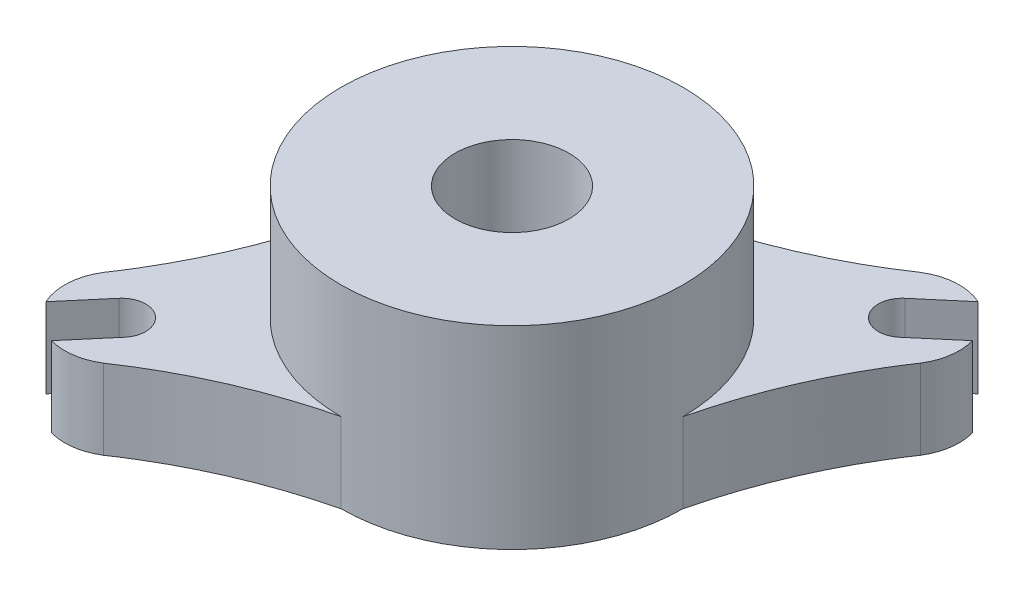
SolidWorks part; units mm, degrees
ref_plane "Front Plane" through (0, 0, 0) normal (0, 0, 1) x (1, 0, 0)
ref_plane "Top Plane" through (0, 0, 0) normal (0, 1, 0) x (1, 0, 0)
ref_plane "Right Plane" through (0, 0, 0) normal (1, 0, 0) x (0, 0, -1)
sketch "Sketch1" plane through (0, 0, 0) normal (0, 1, 0) x (1, 0, 0)
  line L0 (0, 0) -> (-25.3468, 25.3468) construction
  line L1 (21.7322, 21.7322) -> (-21.7322, -21.7322) construction
  circle A0 centre (0, 0) radius 19.05
  circle A1 centre (0, 0) radius 6.35
  circle A2 centre (21.7322, 21.7322) radius 2.667
  circle A3 centre (-21.7322, -21.7322) radius 2.667
  arc A4 (26.8844, 18.0205) -> (18.0205, 26.8844) centre (21.7322, 21.7322) ccw
  arc A5 (-26.8844, -18.0205) -> (-18.0205, -26.8844) centre (-21.7322, -21.7322) ccw
  spline S0 degree 2 poles (0, 19.05) (10.0975, 21.5258) (18.3794, 27.1249) knots 0 0 0 0.663462 0.663462 0.663462
  spline S1 degree 2 poles (19.05, 0) (21.5258, 10.0975) (27.1249, 18.3794) knots 0 0 0 0.663462 0.663462 0.663462
  spline S2 degree 2 poles (0, -19.05) (-10.0975, -21.5258) (-18.3794, -27.1249) knots 0 0 0 0.663462 0.663462 0.663462
  spline S3 degree 2 poles (-19.05, 0) (-21.5258, -10.0975) (-27.1249, -18.3794) knots 0 0 0 0.663462 0.663462 0.663462
  dimension "D1" = 38.1
  dimension "D2" = 12.7
  dimension "D5" = 5.334
  dimension "D6" = 5.334
  dimension "D7" = 12.7
  dimension "D8" = 12.7
  dimension "D3" = 30.734
  dimension "D4" = 30.734
extrude "Boss-Extrude1" add sketch "Sketch1" along normal blind 21.59 contours A0 A1 | A0 S3 A5 S2 A3 | A0 S1 A4 S0 A2
sketch "Sketch2" plane through (0, 21.59, 0) normal (0, 1, 0) x (1, 0, 0)
  circle A0 centre (0, 0) radius 19.05
  spline M4 degree 2 poles (19.05, 0) (21.5258, 10.0975) (27.1249, 18.3794) knots 0 0 0 0.663462 0.663462 0.663462
  arc M5 (27.1249, 18.3794) -> (18.3794, 27.1249) centre (21.7322, 21.7322) ccw
  spline M6 degree 2 poles (18.3794, 27.1249) (10.0975, 21.5258) (0, 19.05) knots 0 0 0 0.663462 0.663462 0.663462
  spline M8 degree 2 poles (-19.05, 0) (-21.5258, -10.0975) (-27.1249, -18.3794) knots 0 0 0 0.663462 0.663462 0.663462
  arc M9 (-27.1249, -18.3794) -> (-18.3794, -27.1249) centre (-21.7322, -21.7322) ccw
  spline M10 degree 2 poles (-18.3794, -27.1249) (-10.0975, -21.5258) (0, -19.05) knots 0 0 0 0.663462 0.663462 0.663462
  circle M11 centre (-21.7322, -21.7322) radius 2.667
  circle M12 centre (21.7322, 21.7322) radius 2.667
extrude "Cut-Extrude1" cut sketch "Sketch2" against normal blind 12.7 contours A0 M8 M9 M10 M11 | A0 M4 M5 M6 M12
sketch "Sketch3" plane through (0, 8.89, 0) normal (0, 1, 0) x (1, 0, 0)
  line L0 (20.0061, 23.7653) -> (24.3992, 27.495)
  line L2 (27.8514, 23.4288) -> (23.4583, 19.6991)
  circle A0 centre (21.7322, 21.7322) radius 2.667 construction
  arc A1 (27.1249, 18.3794) -> (18.3794, 27.1249) centre (21.7322, 21.7322) ccw construction
  arc M5 (27.1249, 18.3794) -> (18.3794, 27.1249) centre (21.7322, 21.7322) ccw
  circle M7 centre (21.7322, 21.7322) radius 2.667
extrude "Cut-Extrude2" cut sketch "Sketch3" along direction (0, -1, 0) on the side against the normal through all contours L2 L0 M5 M7
sketch "Sketch4" plane through (0, 8.89, 0) normal (0, 1, 0) x (1, 0, 0)
  line L0 (-23.7653, -20.0061) -> (-27.495, -24.3992)
  line L1 (-19.6991, -23.4583) -> (-23.4288, -27.8514)
  circle A0 centre (-21.7322, -21.7322) radius 2.667 construction
  arc A1 (-27.1249, -18.3794) -> (-18.3794, -27.1249) centre (-21.7322, -21.7322) ccw construction
  arc M5 (-27.1249, -18.3794) -> (-18.3794, -27.1249) centre (-21.7322, -21.7322) ccw
  circle M7 centre (-21.7322, -21.7322) radius 2.667
extrude "Cut-Extrude3" cut sketch "Sketch4" against normal through all contours L1 L0 M7 M5
